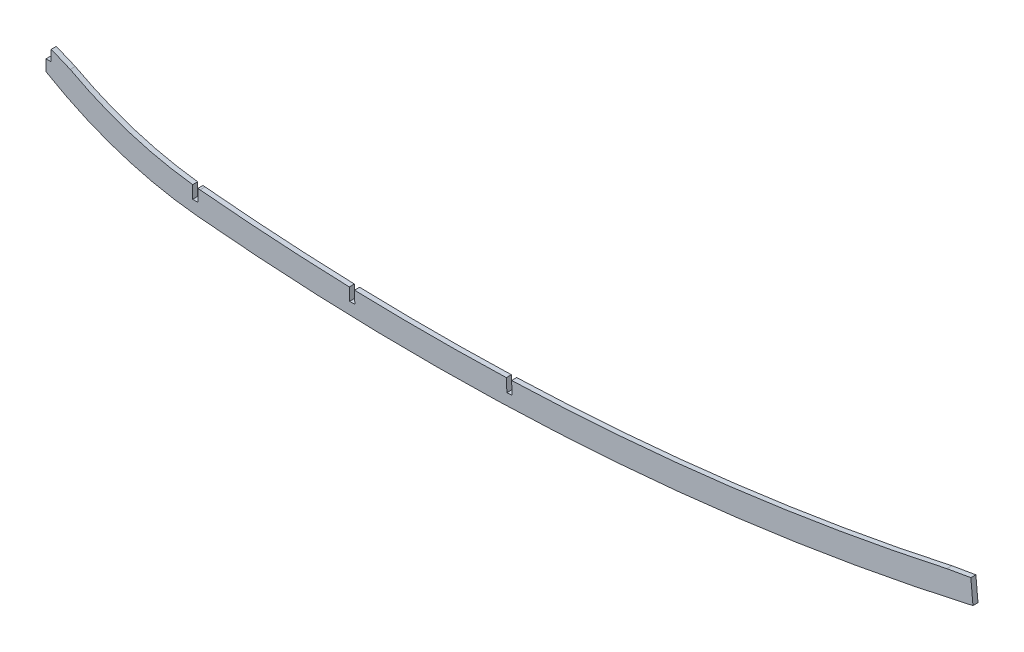
SolidWorks part; units mm, degrees
material "Balsa"
ref_plane "Front Plane" through (0, 0, 0) normal (0, 0, 1) x (1, 0, 0)
ref_plane "Top Plane" through (0, 0, 0) normal (0, 1, 0) x (1, 0, 0)
ref_plane "Right Plane" through (0, 0, 0) normal (1, 0, 0) x (0, 0, -1)
sketch "Sketch1" plane through (0, 0, 0) normal (0, 0, 1) x (1, 0, 0)
  line L0 (0, -90.6646) -> (3.302, -90.6646)
  line L2 (0, -90.8957) -> (0, -97.6692) construction
  line L3 (95.5675, -129.289) -> (95.5675, 69.5372) construction
  line L4 (583.5225, -97.0035) -> (582.3692, -84.3542)
  line L5 (566.0863, 94.2498) -> (564.9329, 106.9009)
  line L6 (92.329, -121.0785) -> (92.329, -113.0996)
  line L7 (583.5225, -97.0035) -> (582.3692, -84.3542) construction
  line L8 (95.631, -121.0785) -> (95.631, -113.4585)
  line L9 (0, -97.6692) -> (0, -90.6646)
  line L13 (0, -194.8379) -> (0, 194.8379) construction
  line L14 (293.3709, -127.4502) -> (292.9452, -117.5593)
  line L15 (282.5516, 123.9503) -> (281.7978, 141.4649)
  line L16 (95.5675, -128.7646) -> (95.5675, -113.5246) construction
  line L17 (293.3709, -127.4502) -> (292.9452, -117.5593) construction
  line L18 (392.833, -129.2657) -> (391.7051, -112.2829)
  line L19 (376.2901, 119.8356) -> (375.1623, 136.8183)
  line L20 (583.5225, -97.0035) -> (582.1925, -82.4157)
  line L21 (392.833, -129.2657) -> (391.7051, -112.2829) construction
  line L22 (469.3335, 125.3653) -> (470.7172, 110.1874)
  line L23 (489.8364, -99.5268) -> (491.2202, -114.7053)
  line L24 (489.8364, -99.5268) -> (491.2202, -114.7053) construction
  line L25 (567.1294, -85.0495) -> (582.1925, -82.4157)
  line L26 (3.302, -83.8066) -> (15.24, -88.7866)
  line L27 (15.24, -88.7866) -> (15.24, -82.4292) construction
  line L28 (3.302, -90.6646) -> (3.302, -78.5632) construction
  line L29 (567.1294, -85.0495) -> (567.0155, -83.7993) construction
  line L30 (92.3925, 69.5372) -> (92.3925, -129.289) construction
  line L31 (3.302, -83.8066) -> (-3.5065, -83.8066) construction
  line L32 (3.302, -90.6646) -> (3.302, -83.8066)
  line L33 (0, -90.6646) -> (0, -83.8066) construction
  line L34 (0, -83.8066) -> (0, -82.4292) construction
  line L35 (0, -97.6692) -> (0, -82.4292) construction
  line L36 (0, -82.4292) -> (3.302, -83.8066) construction
  line L37 (95.631, -113.4585) -> (92.329, -113.4585) construction
  line L38 (92.3925, -121.1448) -> (95.5675, -121.1448) construction
  line L39 (92.3925, -116.3294) -> (95.5675, -116.3294) construction
  line L40 (93.98, -116.3294) -> (93.98, -111.9885) construction
  line L41 (92.329, -121.0785) -> (95.631, -121.0785)
  line L42 (194.3285, -127.3487) -> (194.131, -117.9152)
  line L43 (189.0725, 123.7382) -> (188.7162, 140.7588)
  line L44 (191.1521, -127.4152) -> (190.9546, -117.9783)
  line L45 (185.8962, 123.6683) -> (185.5399, 140.6893)
  line L46 (191.1521, -127.4152) -> (194.3285, -127.3487)
  line L54 (191.1521, -127.4152) -> (194.3285, -127.3487) construction
  line L60 (191.1521, -127.4152) -> (190.9546, -117.9783) construction
  line L63 (194.3285, -127.3487) -> (194.131, -117.9152) construction
  line L65 (190.9546, -117.9783) -> (194.3285, -127.3487) construction
  line L66 (192.6415, -122.6635) -> (192.5195, -116.8324) construction
  line L67 (190.9249, -119.5459) -> (191.088, -127.3372)
  line L69 (194.2298, -119.6498) -> (194.3893, -127.2681)
  line L70 (191.088, -127.3372) -> (194.3893, -127.2681)
  line L71 (194.2262, -119.4768) -> (194.2298, -119.6498) construction
  line L72 (293.3709, -127.4502) -> (290.19, -127.5871)
  line L73 (278.6172, 141.3226) -> (279.371, 123.8073)
  line L74 (289.7641, -117.6901) -> (290.19, -127.5871)
  line L75 (281.7978, 141.4649) -> (282.5516, 123.9503)
  line L76 (292.9452, -117.5593) -> (293.3709, -127.4502)
  line L77 (292.9452, -117.5593) -> (293.3709, -127.4502) construction
  line L79 (289.8445, -119.5584) -> (290.19, -127.5871) construction
  line L81 (293.3709, -127.4502) -> (290.19, -127.5871) construction
  line L82 (290.19, -127.5871) -> (292.9452, -117.5593) construction
  line L83 (291.5676, -122.5732) -> (291.1602, -113.1072) construction
  line L84 (293.4306, -127.4626) -> (293.0858, -119.4503)
  line L85 (290.1316, -127.6046) -> (289.7854, -119.5603)
  line L86 (290.1316, -127.6046) -> (293.4306, -127.4626)
  line L87 (289.7854, -119.5603) -> (289.7547, -118.847) construction
  line L88 (289.7641, -117.6901) -> (289.8445, -119.5584) construction
  line L89 (293.0858, -119.4503) -> (293.0537, -118.7051) construction
  arc A0 (95.5675, -128.7646) -> (583.5225, -97.0035) centre (240.5771, 1407.5883) ccw
  arc A1 (0, -97.6692) -> (95.5675, -128.7646) centre (117.1596, 100) ccw
  arc A2 (15.24, -88.7866) -> (92.329, -113.0996) centre (117.1596, 100) ccw
  arc A3 (96.9996, -113.5921) -> (190.9249, -119.5459) centre (240.5771, 1407.5883) ccw
  arc A4 (92.329, -113.0996) -> (93.98, -113.2855) centre (117.1596, 100) ccw construction
  arc A5 (95.631, -113.4585) -> (96.9996, -113.5921) centre (117.1596, 100) ccw
  arc A6 (15.24, -88.7866) -> (96.9996, -113.5921) centre (117.1596, 100) ccw construction
  arc A7 (93.98, -113.2855) -> (95.631, -113.4585) centre (117.1596, 100) ccw construction
  arc A9 (192.5197, -119.5969) -> (192.5774, -119.5987) centre (240.5771, 1407.5883) ccw construction
  arc A10 (96.9996, -113.5921) -> (567.1294, -85.0495) centre (240.5771, 1407.5883) ccw construction
  arc A11 (192.5774, -119.5987) -> (194.1673, -119.6479) centre (240.5771, 1407.5883) ccw construction
  arc A12 (194.2298, -119.6498) -> (289.7854, -119.5603) centre (240.5771, 1407.5883) ccw
  arc A13 (194.1673, -119.6479) -> (194.2298, -119.6498) centre (240.5771, 1407.5883) ccw construction
  arc A14 (190.9249, -119.5459) -> (190.9874, -119.5479) centre (240.5771, 1407.5883) ccw construction
  arc A15 (191.526, -119.5653) -> (192.5197, -119.5969) centre (240.5771, 1407.5883) ccw construction
  arc A16 (190.9874, -119.5479) -> (191.526, -119.5653) centre (240.5771, 1407.5883) ccw construction
  arc A17 (289.8445, -119.5584) -> (291.4356, -119.5062) centre (240.5771, 1407.5883) ccw construction
  arc A18 (293.0858, -119.4503) -> (567.1294, -85.0495) centre (240.5771, 1407.5883) ccw
  arc A19 (289.7854, -119.5603) -> (289.8445, -119.5584) centre (240.5771, 1407.5883) ccw construction
  arc A20 (291.4356, -119.5062) -> (292.4194, -119.4731) centre (240.5771, 1407.5883) ccw construction
  arc A21 (292.4194, -119.4731) -> (293.0267, -119.4524) centre (240.5771, 1407.5883) ccw construction
  arc A22 (293.0267, -119.4524) -> (293.0858, -119.4503) centre (240.5771, 1407.5883) ccw construction
  spline S0 degree 3 poles (1163.1173, 139.9242) (513.5517, 132.7413) (-159.1095, 117.8773) (-795.5456, 96.6485) knots -312.056532 -312.056532 -312.056532 -312.056532 318.543678 318.543678 318.543678 318.543678 weights 1.022155 0.992356 0.992617 1.02294 only from (189.0725, 123.7382) to (185.8962, 123.6683)
  spline S1 degree 3 poles (-1654.4878, -133.9919) (-536.4165, -139.6451) (839.2921, -112.8551) (2017.9083, -62.3191) knots -640.842615 -640.842615 -640.842615 -640.842615 619.906354 619.906354 619.906354 619.906354 weights 1.093283 0.971033 0.968942 1.087011 only from (190.9546, -117.9783) to (194.131, -117.9152)
  spline S2 degree 3 poles (582.7117, -81.452) (582.6874, -81.5022) (582.6416, -81.5954) (582.5542, -81.7672) (582.4594, -81.9475) (582.3482, -82.151) (582.2047, -82.3991) (581.9733, -82.7697) (581.6781, -83.1881) (581.1944, -83.7591) (580.5687, -84.2887) (579.0051, -84.9672) (576.4459, -83.7497) (572.7578, -77.4718) (568.9823, -66.8681) (565.3193, -52.5029) (561.9524, -35.0804) (559.7866, -20.4045) (558.5401, -10.2658) (558.0552, -5.9951) (557.6897, -2.566) (557.4695, -0.4059) (557.3018, 1.2957) (557.171, 2.6577) (557.0444, 4.0056) (556.973, 4.7862) (556.9363, 5.1913) knots 0.000015 0.000015 0.000015 0.000015 0.003921 0.007827 0.011733 0.015639 0.023452 0.031264 0.046889 0.062514 0.093763 0.125013 0.250011 0.375009 0.500007 0.625005 0.750004 0.875002 0.906251 0.937501 0.953126 0.96875 0.976563 0.984375 0.992188 1 1 1 1 construction
  spline S3 degree 3 poles (1168.5569, 157.5503) (514.9793, 149.5181) (-156.4878, 134.7902) (-800.1199, 114.3723) knots -312.673321 -312.673321 -312.673321 -312.673321 317.888322 317.888322 317.888322 317.888322 weights 1.017089 0.99415 0.994305 1.017552 only from (188.7162, 140.7588) to (185.5399, 140.6893)
  spline S4 degree 3 poles (1717.4326, 1.4774) (898.7054, -133.6627) (-633.1313, -185.0676) (-1185.4559, -104.0981) knots -589.349316 -589.349316 -589.349316 -589.349316 680.325331 680.325331 680.325331 680.325331 weights 1.332969 0.855149 0.891593 1.442299 only from (292.9452, -117.5593) to (289.7641, -117.6901)
  spline S5 degree 3 poles (190.9546, -117.9783) (192.0134, -117.9573) (193.0722, -117.9362) (194.131, -117.9152) knots 0 0 0 0 1 1 1 1 weights 1 1 1 1 construction
  spline S6 degree 3 poles (-652.4097, 59.5092) (-102.6126, 113.9617) (587.244, 146.1283) (1177.6485, 144.4873) knots -325.910165 -325.910165 -325.910165 -325.910165 304.77209 304.77209 304.77209 304.77209 weights 1.101964 0.970622 0.966168 1.088602 only from (279.371, 123.8073) to (282.5516, 123.9503)
  spline S7 degree 3 poles (1198.9369, 164.6773) (592.9142, 162.5971) (-91.2213, 131.2532) (-668.7462, 79.2936) knots -306.100996 -306.100996 -306.100996 -306.100996 323.941925 323.941925 323.941925 323.941925 weights 1.068615 0.974615 0.977197 1.07636 only from (281.7978, 141.4649) to (278.6172, 141.3226)
  spline S10 degree 3 poles (292.9452, -117.5593) (291.8848, -117.603) (290.8244, -117.6465) (289.7641, -117.6901) knots 0 0 0 0 1 1 1 1 weights 1 1 1 1 construction
  point P63 (93.98, -113.4585)
  point P75 (194.2298, -119.6498)
  point P92 (289.7854, -119.5603)
  dimension "D1" = 100
  dimension "D5" = 15.24
  dimension "D6" = 82.4292
  dimension "D2" = 15.24
  dimension "D3" = 15.24
  dimension "D4" = 14.6483
  dimension "D7" = 3.302
  dimension "D8" = 6.858
  dimension "D9" = 38.1
  dimension "D10" = 3.302
  dimension "D11" = 7.62
  dimension "D12" = 7.62
  dimension "D13" = 3.302
  dimension "D14" = 3.302
  dimension "D15" = 8.0518
extrude "Boss-Extrude1" add sketch "Sketch1" along normal mid plane 3.175
equation "\"slotwidth\"=0.197118"
